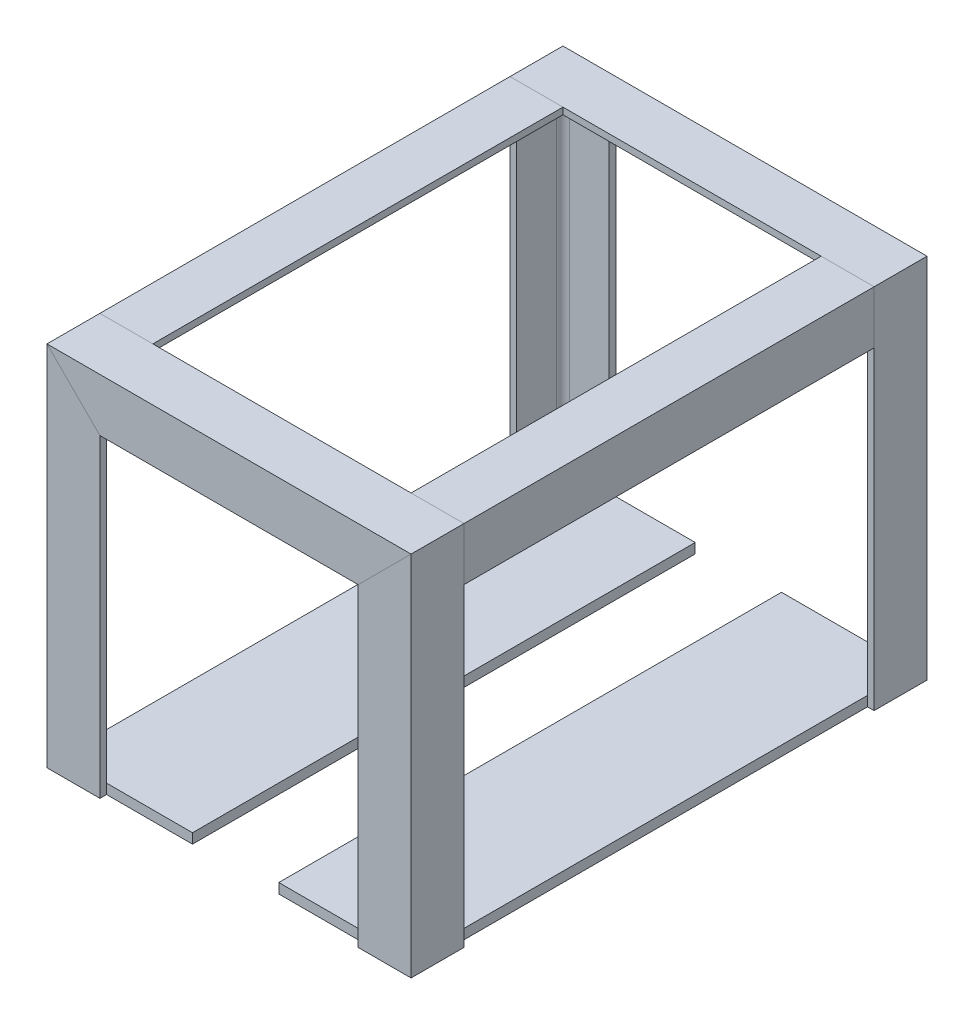
SolidWorks part; units mm, degrees
ref_plane "Alzado" through (0, 0, 0) normal (0, 0, 1) x (1, 0, 0)
ref_plane "Planta" through (0, 0, 0) normal (0, 1, 0) x (1, 0, 0)
ref_plane "Vista lateral" through (0, 0, 0) normal (1, 0, 0) x (0, 0, -1)
sketch3d "Croquis3D1"
  line L0 (0, 0, 0) -> (0, 225.552, 0)
  line L1 (0, 225.552, 0) -> (174.752, 225.552, 0)
  line L2 (174.752, 225.552, 0) -> (174.752, 0, 0)
  line L3 (174.752, 0, 0) -> (0, 0, 0) construction
  line L4 (174.752, 225.552, 0) -> (174.752, 225.552, 247.65)
  line L5 (0, 225.552, 0) -> (0, 225.552, 247.65)
  line L6 (0, 225.552, 247.65) -> (174.752, 225.552, 247.65)
  line L7 (174.752, 225.552, 247.65) -> (174.752, 0, 247.65)
  line L9 (0, 225.552, 247.65) -> (0, 0, 247.65)
  dimension "D1" = 225.552
  dimension "D2" = 174.752
  dimension "D3" = 247.65
other "Ángulo de extremos cuadrados al ls AL LS ANGLE SQR END 1 X 1 X 0.125(1)"
ref_plane "Plano2" through (0, 0, 0) normal (0, -1, 0) x (1, 0, 0)
sketch "Sketch1" plane through (0, 0, 0) normal (0, -1, 0) x (1, 0, 0)
  line L0 (0, 0) -> (0, 25.4)
  line L2 (3.175, 25.4) -> (3.175, 6.35)
  line L3 (6.35, 3.175) -> (25.4, 3.175)
  line L5 (25.4, 0) -> (0, 0)
  line L6 (0, 25.4) -> (3.175, 25.4)
  line L7 (25.4, 0) -> (25.4, 3.175)
  arc A2 (6.35, 3.175) -> (3.175, 6.35) centre (6.35, 6.35) cw
  point P1 (0, 0)
  point P10 (0, 12.7)
  point P11 (12.7, 0)
  dimension "Radius_1" = 3.175
  dimension "V_leg" = 25.4
  dimension "H_leg" = 25.4
  dimension "Thickness" = 3.175
other "Ángulo de extremos cuadrados al ls AL LS ANGLE SQR END 1 X 1 X 0.125(4)"
ref_plane "Plano4" through (174.752, 225.552, 247.65) normal (0, 1, 0) x (0, 0, -1)
sketch "Sketch12" plane through (174.752, 225.552, 247.65) normal (0, 1, 0) x (0, 0, -1)
  line L0 (0, 0) -> (0, 25.4)
  line L2 (3.175, 25.4) -> (3.175, 6.35)
  line L3 (6.35, 3.175) -> (25.4, 3.175)
  line L5 (25.4, 0) -> (0, 0)
  line L6 (0, 25.4) -> (3.175, 25.4)
  line L7 (25.4, 0) -> (25.4, 3.175)
  arc A2 (6.35, 3.175) -> (3.175, 6.35) centre (6.35, 6.35) cw
  point P1 (0, 0)
  point P10 (0, 12.7)
  point P11 (12.7, 0)
  dimension "Radius_1" = 3.175
  dimension "V_leg" = 25.4
  dimension "H_leg" = 25.4
  dimension "Thickness" = 3.175
sketch3d "Croquis3D2"
  line L0 (174.752, 225.552, 25.4) -> (174.752, 225.552, 222.25)
  line L1 (0, 225.552, 222.25) -> (0, 225.552, 25.4)
other "Ángulo de extremos cuadrados al ls AL LS ANGLE SQR END 1 X 1 X 0.125(5)"
ref_plane "Plano5" through (174.752, 225.552, 25.4) normal (0, 0, 1) x (-1, 0, 0)
sketch "Sketch13" plane through (174.752, 225.552, 25.4) normal (0, 0, 1) x (-1, 0, 0)
  line L0 (0, 0) -> (0, 25.4)
  line L2 (3.175, 25.4) -> (3.175, 6.35)
  line L3 (6.35, 3.175) -> (25.4, 3.175)
  line L5 (25.4, 0) -> (0, 0)
  line L6 (0, 25.4) -> (3.175, 25.4)
  line L7 (25.4, 0) -> (25.4, 3.175)
  arc A2 (6.35, 3.175) -> (3.175, 6.35) centre (6.35, 6.35) cw
  point P1 (0, 0)
  point P10 (0, 12.7)
  point P11 (12.7, 0)
  dimension "Radius_1" = 3.175
  dimension "V_leg" = 25.4
  dimension "H_leg" = 25.4
  dimension "Thickness" = 3.175
other "Ángulo de extremos cuadrados al ls AL LS ANGLE SQR END 1 X 1 X 0.125(6)"
ref_plane "Plano6" through (0, 225.552, 222.25) normal (0, 0, -1) x (1, 0, 0)
sketch "Sketch14" plane through (0, 225.552, 222.25) normal (0, 0, -1) x (1, 0, 0)
  line L0 (0, 0) -> (0, 25.4)
  line L2 (3.175, 25.4) -> (3.175, 6.35)
  line L3 (6.35, 3.175) -> (25.4, 3.175)
  line L5 (25.4, 0) -> (0, 0)
  line L6 (0, 25.4) -> (3.175, 25.4)
  line L7 (25.4, 0) -> (25.4, 3.175)
  arc A2 (6.35, 3.175) -> (3.175, 6.35) centre (6.35, 6.35) cw
  point P1 (0, 0)
  point P10 (0, 12.7)
  point P11 (12.7, 0)
  dimension "Radius_1" = 3.175
  dimension "V_leg" = 25.4
  dimension "H_leg" = 25.4
  dimension "Thickness" = 3.175
ref_plane "Plano7" through (0, 54.102, 0) normal (0, -1, 0) x (-1, 0, 0)
sketch "Croquis3" plane through (0, 54.102, 0) normal (0, -1, 0) x (-1, 0, 0)
  line L0 (-168.402, -244.475) -> (-108.077, -244.475)
  line L1 (-168.402, -244.475) -> (-6.35, -244.475) construction
  line L2 (-108.077, -244.475) -> (-108.077, -3.175)
  line L3 (-168.402, -3.175) -> (-6.35, -3.175) construction
  line L4 (-108.077, -3.175) -> (-168.402, -3.175)
  line L5 (-171.577, -6.35) -> (-171.577, -241.3)
  line L6 (-87.376, -247.65) -> (-87.376, -207.071) construction
  line L7 (-149.352, -247.65) -> (-25.4, -247.65) construction
  line L8 (-66.675, -3.175) -> (-6.35, -3.175)
  line L9 (-66.675, -244.475) -> (-66.675, -3.175)
  line L10 (-6.35, -244.475) -> (-66.675, -244.475)
  line L11 (-3.175, -6.35) -> (-3.175, -241.3)
  arc A0 (-171.577, -241.3) -> (-168.402, -244.475) centre (-168.402, -241.3) ccw
  arc A1 (-171.577, -241.3) -> (-168.402, -244.475) centre (-168.402, -241.3) ccw construction
  arc A2 (-168.402, -3.175) -> (-171.577, -6.35) centre (-168.402, -6.35) ccw
  arc A3 (-6.35, -3.175) -> (-3.175, -6.35) centre (-6.35, -6.35) cw
  arc A4 (-3.175, -241.3) -> (-6.35, -244.475) centre (-6.35, -241.3) cw
  dimension "D1" = 63.5
extrude "Saliente-Extruir1" add sketch "Croquis3" along normal blind 4.7625 separate body
sketch "Croquis4" plane through (0, 0, 0) normal (-1, 0, 0) x (0, 0, 1)
  line L0 (247.65, 225.552) -> (247.65, 0) construction
  line L1 (247.65, 49.3395) -> (0, 49.3395)
  line L2 (247.65, 49.3395) -> (247.65, 0)
  line L3 (247.65, 0) -> (0, 0)
  line L4 (0, 49.3395) -> (0, 0)
  line L6 (241.3, 49.3395) -> (6.35, 49.3395) construction
extrude "Cortar-Extruir1" cut sketch "Croquis4" against normal through all
